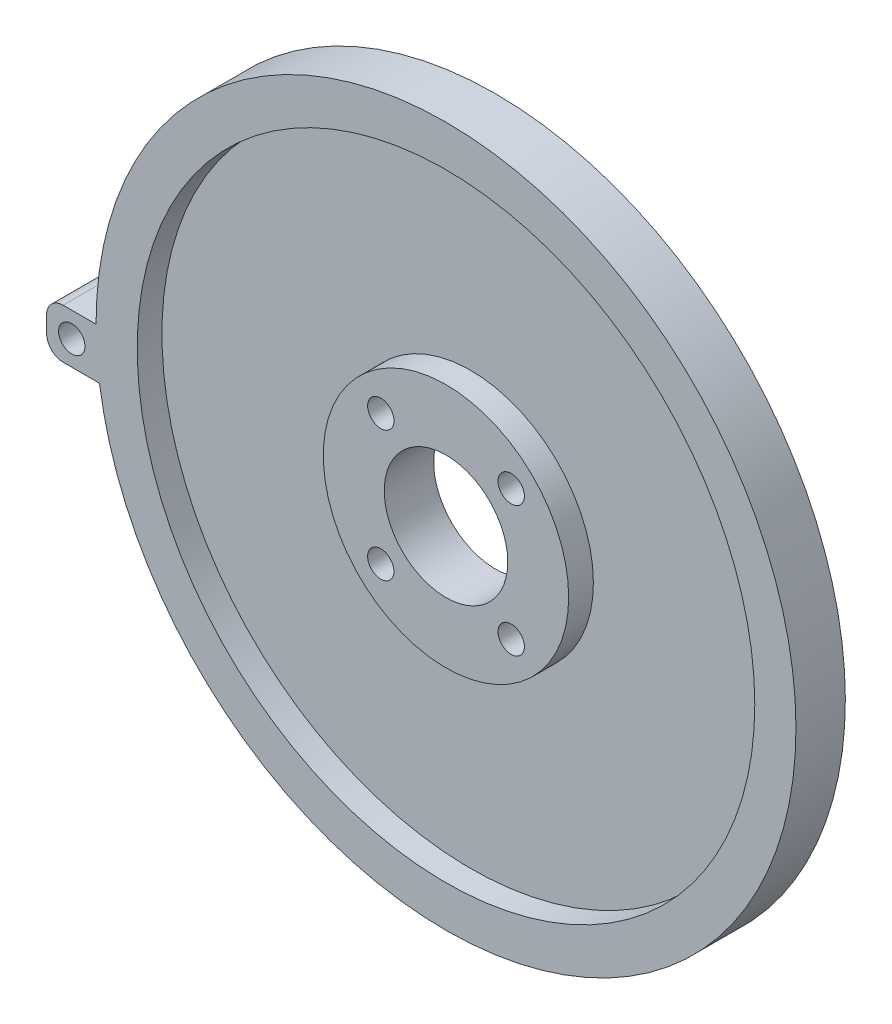
SolidWorks part; units mm, degrees
ref_plane "Front Plane" through (0, 0, 0) normal (0, 0, 1) x (1, 0, 0)
ref_plane "Top Plane" through (0, 0, 0) normal (0, 1, 0) x (1, 0, 0)
ref_plane "Right Plane" through (0, 0, 0) normal (1, 0, 0) x (0, 0, -1)
sketch "Sketch1" plane through (0, 0, 0) normal (0, 0, 1) x (1, 0, 0)
  circle A1 centre (260.117, -9.1) radius 42.5
  circle A6 centre (252.1974, -1.1804) radius 1.6
  circle A7 centre (268.0366, -1.1804) radius 1.6
  circle A8 centre (252.1974, -17.0196) radius 1.6
  circle A9 centre (268.0366, -17.0196) radius 1.6
  circle A11 centre (260.117, -9.1) radius 7.5
extrude "Boss-Extrude1" add sketch "Sketch1" along normal blind 3
sketch "Sketch3" plane through (0, 0, 3) normal (0, 0, 1) x (1, 0, 0)
  circle A1 centre (260.117, -9.1) radius 7.5
  circle A2 centre (260.117, -9.1) radius 7.5
  circle A3 centre (268.0366, -17.0196) radius 1.6
  circle A4 centre (268.0366, -17.0196) radius 1.6
  circle A5 centre (252.1974, -17.0196) radius 1.6
  circle A6 centre (252.1974, -17.0196) radius 1.6
  circle A7 centre (268.0366, -1.1804) radius 1.6
  circle A8 centre (268.0366, -1.1804) radius 1.6
  circle A9 centre (252.1974, -1.1804) radius 1.6
  circle A10 centre (252.1974, -1.1804) radius 1.6
  circle A11 centre (260.117, -9.1) radius 14.9
  circle A13 centre (260.117, -9.1) radius 42.5 construction
  circle A14 centre (260.117, -9.1) radius 42.5
  circle A15 centre (260.117, -9.1) radius 37.5
  circle M7 centre (252.1974, -17.0196) radius 1.6
  circle M8 centre (252.1974, -1.1804) radius 1.6
  circle M9 centre (260.117, -9.1) radius 42.5
  circle M10 centre (260.117, -9.1) radius 7.5
  circle M11 centre (268.0366, -1.1804) radius 1.6
  circle M12 centre (268.0366, -17.0196) radius 1.6
  dimension "D1" = 0
  dimension "D2" = 0
  dimension "D3" = 0
  dimension "D4" = 0
  dimension "D5" = 0
  dimension "D6" = 5
extrude "Boss-Extrude2" add sketch "Sketch3" along normal blind 3 contours A15 M9 | A11 M7 M11 M12 M10 M8
sketch "Sketch4" plane through (0, 0, 3) normal (0, 0, 1) x (1, 0, 0)
  line L1 (217.617, -9.1) -> (213.617, -9.1)
  line L2 (211.617, -11.1) -> (211.617, -13.1)
  line L3 (213.617, -15.1) -> (218.0427, -15.1)
  circle A1 centre (260.117, -9.1) radius 42.5 construction
  arc A2 (217.617, -9.1) -> (218.0427, -15.1) centre (260.117, -9.1) ccw
  circle A3 centre (214.6703, -12.1038) radius 1.6
  arc A4 (211.617, -13.1) -> (213.617, -15.1) centre (213.617, -13.1) ccw
  arc A5 (211.617, -11.1) -> (213.617, -9.1) centre (213.617, -11.1) cw
  dimension "D1" = 2
extrude "Boss-Extrude3" add sketch "Sketch4" along normal up to surface and the other way up to surface up to face at (297.617, -9.1, 6) other way up to face at (302.617, -9.1, 0)
